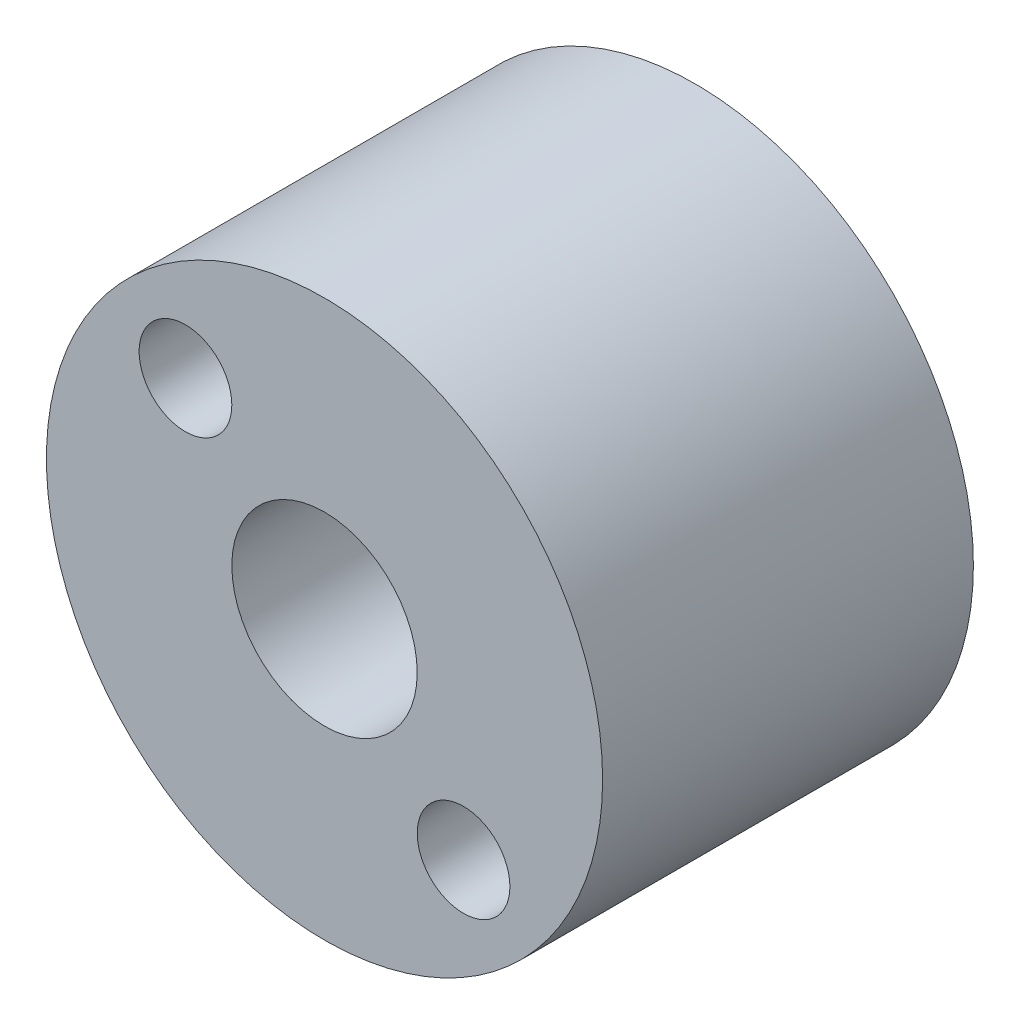
SolidWorks part; units mm, degrees
ref_plane "Vorne" through (0, 0, 0) normal (0, 0, 1) x (1, 0, 0)
ref_plane "Oben" through (0, 0, 0) normal (0, 1, 0) x (1, 0, 0)
ref_plane "Rechts" through (0, 0, 0) normal (1, 0, 0) x (0, 0, -1)
sketch "Skizze2" plane through (0, 0, 0) normal (0, 0, 1) x (1, 0, 0)
  circle A0 centre (0, 0) radius 15
  dimension "D1" = 30
extrude "Aufsatz-Linear austragen1" add sketch "Skizze2" along normal blind 20
hole_wizard "Ø10.0 (10) Durchmesser Bohrung1" positions "Skizze5" profile "Skizze6" hole size "Ø10.0" standard "DIN" end condition through all
sketch "Skizze5" plane through (0, 0, 20) normal (0, 0, 1) x (1, 0, 0)
  point P0 (0, 0)
sketch "Skizze6" plane through (0, 0, 20) normal (1, 0, 0) x (0, -1, 0)
  line L0 (0, 0) -> (0, 20)
  line L1 (0, 20) -> (5, 20)
  line L2 (5, 20) -> (5, 0)
  line L5 (5, 0) -> (0, 0)
  line L11 (0, -6.35) -> (0, 107.95) construction
  dimension "Bohrerdurchmesser" = 10
  dimension "Bohrungstiefe" = 20
hole_wizard "Ø5.0 (5) Durchmesser Bohrung1" positions "Skizze12" profile "Skizze13" hole size "Ø5.0" standard "DIN" end condition through all
sketch "Skizze12" plane through (0, 0, 20) normal (0, 0, 1) x (1, 0, 0)
  line L0 (-7.5, 7.5) -> (7.7373, 7.5) construction
  line L2 (-7.1906, -7.5) -> (8.5494, -7.5) construction
  line L5 (7.5, -7.5) -> (7.5, 9.1402) construction
  line L8 (-7.5, 7.5) -> (-7.5, -8.1133) construction
  line L11 (0, -11) -> (0, 11) construction
  line L12 (13.75, 0) -> (-13.75, 0) construction
  point P0 (-7.5, 7.5)
  point P2 (7.5, -7.5)
  dimension "D1" = 15
  dimension "D2" = 15
  dimension "D3" = 7.5
  dimension "D4" = 7.5
sketch "Skizze13" plane through (-7.5, 7.5, 20) normal (1, 0, 0) x (0, -1, 0)
  line L0 (0, 0) -> (0, 20)
  line L1 (0, 20) -> (2.5, 20)
  line L2 (2.5, 20) -> (2.5, 0)
  line L5 (2.5, 0) -> (0, 0)
  line L11 (0, -6.35) -> (0, 107.95) construction
  dimension "Bohrerdurchmesser" = 5
  dimension "Bohrungstiefe" = 20
